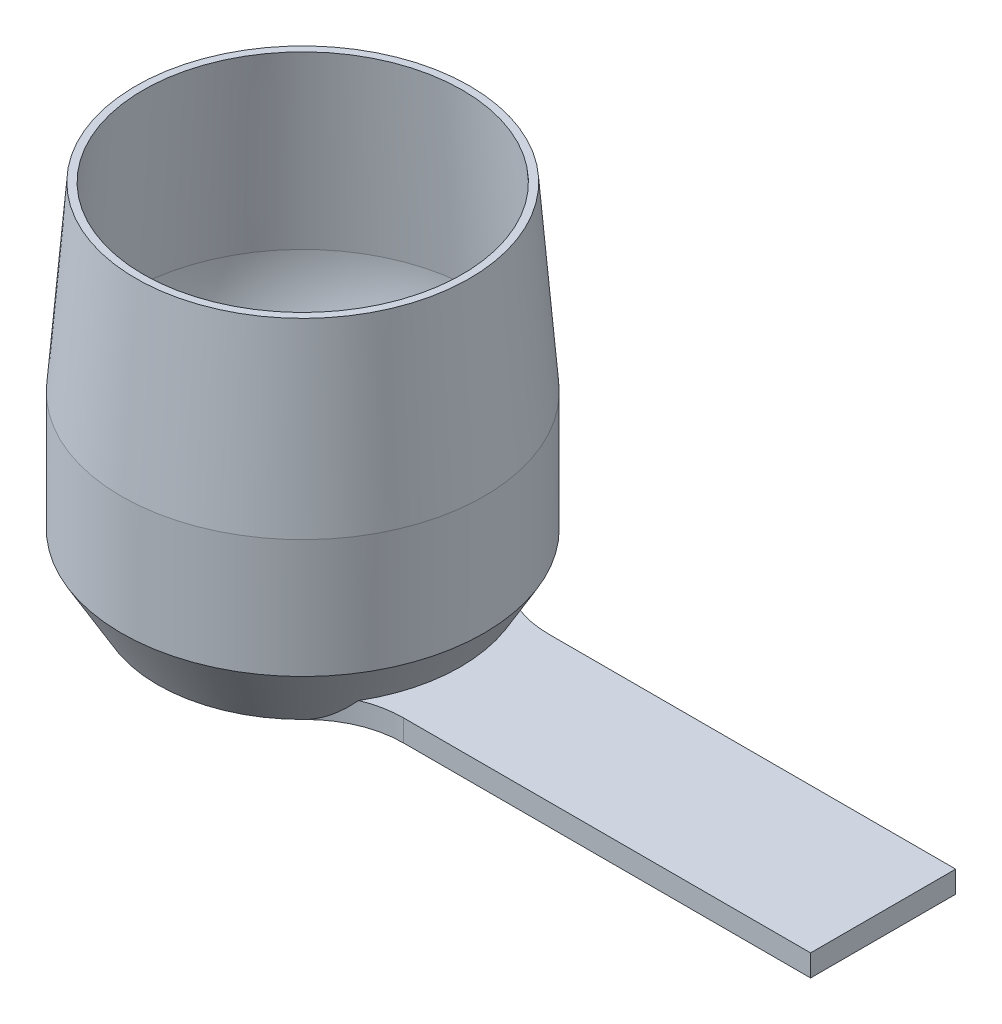
SolidWorks part; units mm, degrees
ref_plane "Front Plane" through (0, 0, 0) normal (0, 0, 1) x (1, 0, 0)
ref_plane "Top Plane" through (0, 0, 0) normal (0, 1, 0) x (1, 0, 0)
ref_plane "Right Plane" through (0, 0, 0) normal (1, 0, 0) x (0, 0, -1)
sketch "Sketch6" plane through (0, 0, 0) normal (1, 0, 0) x (0, 0, -1)
  line L0 (0, 0.6285) -> (0, 26.7591) construction
  line L1 (0, 0) -> (-20, 0)
  line L2 (-25, 8.6603) -> (-25, 25)
  line L3 (-25, 25) -> (-23, 50)
  line L4 (-23, 50) -> (-22, 50)
  line L5 (-22, 50) -> (-24, 25)
  line L7 (0, 0.8) -> (0, 0)
  line L8 (-25, 8.6603) -> (-20, 0)
  arc A1 (-24, 25) -> (0, 0.8) centre (0, 24.8008) ccw
  dimension "D1" = 50
  dimension "D2" = 46
  dimension "D3" = 25
  dimension "D4" = 50
  dimension "D5" = 30
  dimension "D6" = 1
  dimension "D7" = 1
  dimension "D8" = 0.8
  dimension "D9" = 10
  dimension "D10" = 40
revolve "Revolve1" add sketch "Sketch6" angle 360 about L0
sketch "Sketch7" plane through (0, 0, 0) normal (0, 1, 0) x (1, 0, 0)
  line L1 (23.8874, -10) -> (80, -10)
  line L6 (23.8874, 10) -> (80, 10)
  line L7 (80, -10) -> (80, 10)
  arc A8 (23.8874, -10) -> (14.2482, -14.0353) centre (23.8874, -23.5305) ccw
  circle A9 centre (0, 0) radius 20
  arc A10 (14.2482, -14.0353) -> (14.2482, 14.0353) centre (0, 0) ccw
  arc A11 (14.2482, 14.0353) -> (23.8874, 10) centre (23.8874, 23.5305) ccw
  dimension "D1" = 0
  dimension "D2" = 20
  dimension "D3" = 80
extrude "Boss-Extrude2" add sketch "Sketch7" along normal blind 3
